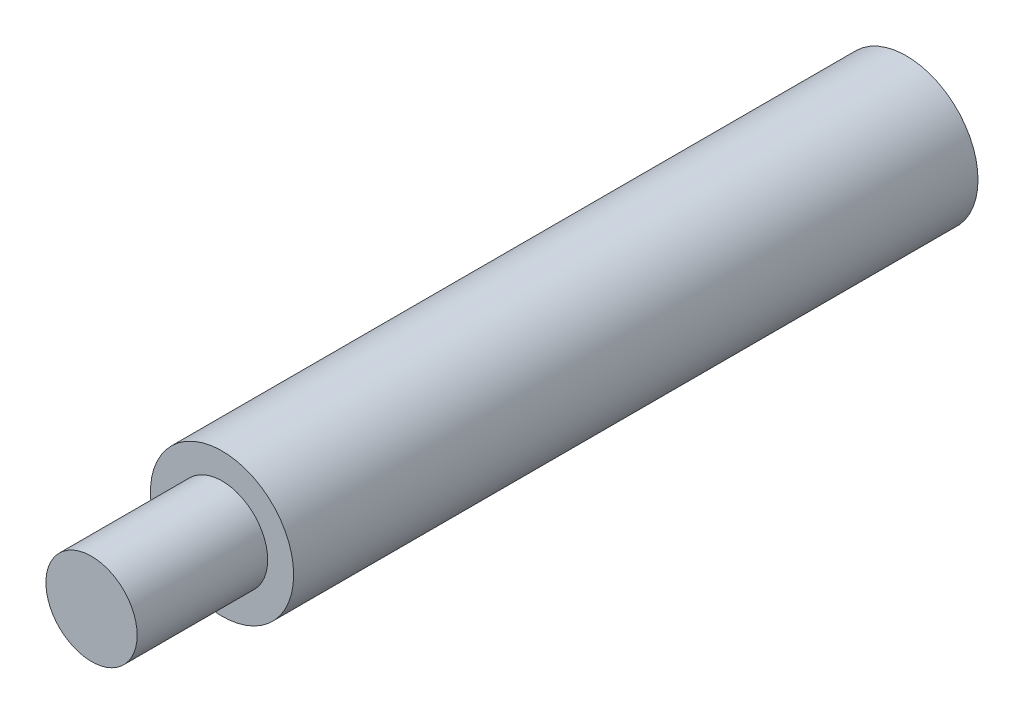
SolidWorks part; units mm, degrees
ref_plane "Front Plane" through (0, 0, 0) normal (0, 0, 1) x (1, 0, 0)
ref_plane "Top Plane" through (0, 0, 0) normal (0, 1, 0) x (1, 0, 0)
ref_plane "Right Plane" through (0, 0, 0) normal (1, 0, 0) x (0, 0, -1)
sketch "Sketch2" plane through (0, 0, 0) normal (0, 0, 1) x (1, 0, 0)
  circle A0 centre (0, 0) radius 1
  dimension "D1" = 2
extrude "Boss-Extrude1" add sketch "Sketch2" along normal blind 17.86 contours A0
sketch "Sketch6" plane through (0, 0, 0) normal (0, 0, 1) x (1, 0, 0)
  circle A0 centre (0, 0) radius 1.57
  dimension "D1" = 3.14
extrude "Boss-Extrude2" add sketch "Sketch6" along normal blind 15
